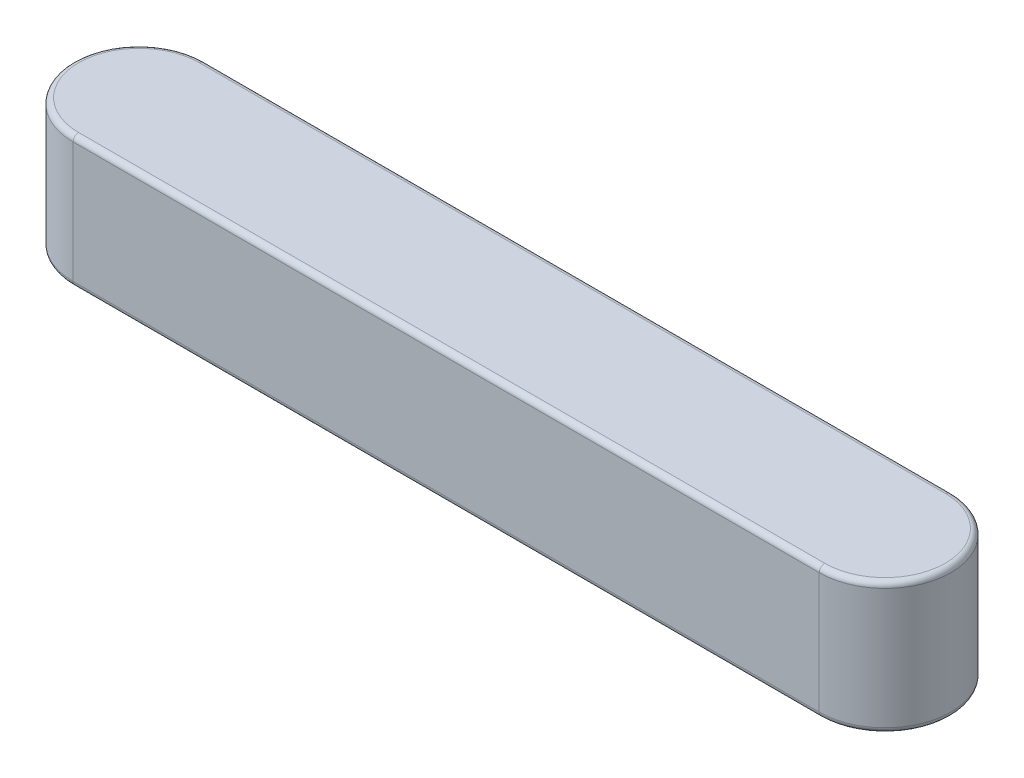
SolidWorks part; units mm, degrees
material "Stahl (grün)"
ref_plane "Front Plane" through (0, 0, 0) normal (0, 0, 1) x (1, 0, 0)
ref_plane "Top Plane" through (0, 0, 0) normal (0, 1, 0) x (1, 0, 0)
ref_plane "Right Plane" through (0, 0, 0) normal (1, 0, 0) x (0, 0, -1)
sketch "Sketch1" plane through (0, 0, 0) normal (0, 1, 0) x (1, 0, 0)
  line L1 (-34, 3) -> (0, 3)
  line L3 (-34, -3) -> (0, -3)
  arc A0 (0, -3) -> (0, 3) centre (0, 0) ccw
  arc A1 (-34, 3) -> (-34, -3) centre (-34, 0) ccw
  dimension "l" = 40
  dimension "b" = 6
extrude "Extrude1" add sketch "Sketch1" along normal blind 6
fillet "Fillet1" radius 0.25 8 edges at (-17, 0, -3) (3, 0, 0) (-37, 0, 0) (-17, 0, 3) (3, 6, 0) (-17, 6, 3) (-17, 6, -3) (-37, 6, 0)
